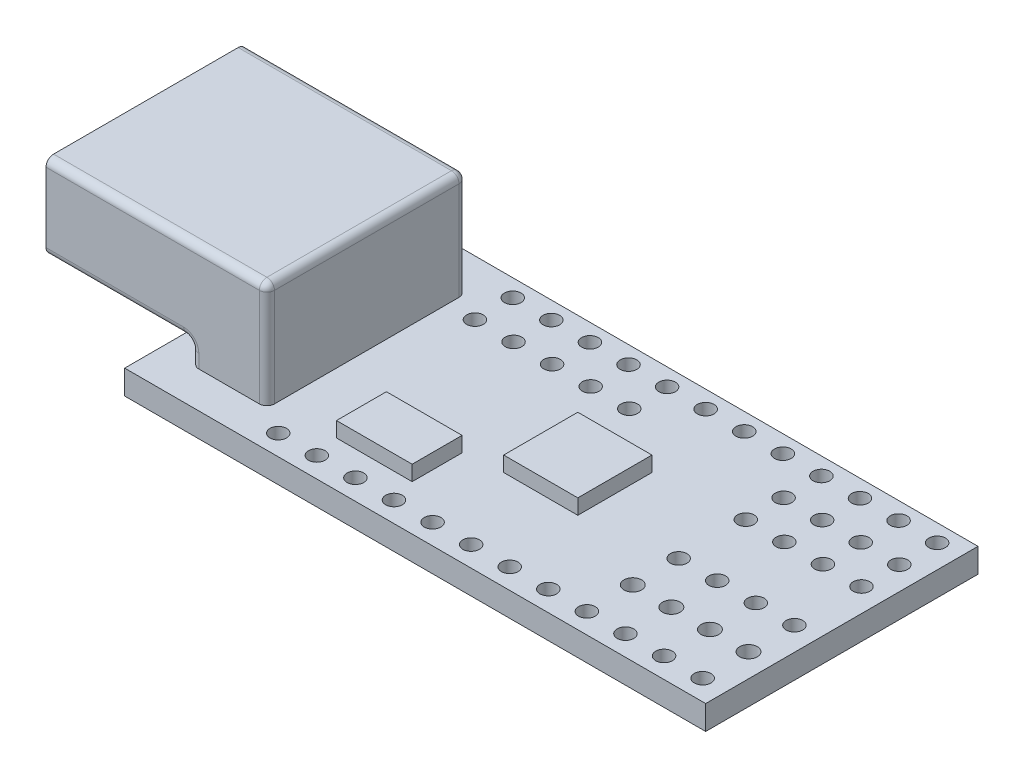
SolidWorks part; units mm, degrees
ref_plane "Plan de face" through (0, 0, 0) normal (0, 0, 1) x (1, 0, 0)
ref_plane "Plan de dessus" through (0, 0, 0) normal (0, 1, 0) x (1, 0, 0)
ref_plane "Plan de droite" through (0, 0, 0) normal (1, 0, 0) x (0, 0, -1)
sketch "Esquisse1" plane through (0, 0, 0) normal (0, 1, 0) x (1, 0, 0)
  line L1 (-19.2, -9) -> (19.2, -9)
  line L2 (-19.2, -9) -> (-19.2, 9)
  line L3 (-19.2, 9) -> (19.2, 9)
  line L4 (19.2, -9) -> (19.2, 9)
  circle A0 centre (17.65, -7.65) radius 0.55
  circle A1 centre (15.1, -7.65) radius 0.55
  circle A2 centre (12.55, -7.65) radius 0.55
  circle A3 centre (10, -7.65) radius 0.55
  circle A4 centre (7.45, -7.65) radius 0.55
  circle A5 centre (4.9, -7.65) radius 0.55
  circle A6 centre (2.35, -7.65) radius 0.55
  circle A7 centre (-0.2, -7.65) radius 0.55
  circle A8 centre (-2.75, -7.65) radius 0.55
  circle A9 centre (-5.3, -7.65) radius 0.55
  circle A10 centre (-7.85, -7.65) radius 0.55
  circle A11 centre (-10.4, -7.65) radius 0.55
  circle A12 centre (17.65, 7.85) radius 0.55
  circle A13 centre (15.1, 7.85) radius 0.55
  circle A14 centre (12.55, 7.85) radius 0.55
  circle A15 centre (10, 7.85) radius 0.55
  circle A16 centre (7.45, 7.85) radius 0.55
  circle A17 centre (4.9, 7.85) radius 0.55
  circle A18 centre (2.35, 7.85) radius 0.55
  circle A19 centre (-0.2, 7.85) radius 0.55
  circle A20 centre (-2.75, 7.85) radius 0.55
  circle A21 centre (-5.3, 7.85) radius 0.55
  circle A22 centre (-7.85, 7.85) radius 0.55
  circle A23 centre (-10.4, 7.85) radius 0.55
  circle A24 centre (17.65, -4.6173) radius 0.5827
  circle A25 centre (17.65, -1.5845) radius 0.55
  circle A26 centre (17.65, 5.35) radius 0.55
  circle A27 centre (17.65, 2.85) radius 0.55
  circle A28 centre (15.1, -4.6173) radius 0.5827
  circle A29 centre (12.55, -4.6173) radius 0.5827
  circle A30 centre (10, -4.6173) radius 0.5827
  circle A31 centre (15.1, -1.5845) radius 0.55
  circle A32 centre (12.55, -1.5845) radius 0.55
  circle A33 centre (10, -1.5845) radius 0.55
  circle A34 centre (15.1, 5.35) radius 0.55
  circle A35 centre (15.1, 2.85) radius 0.55
  circle A36 centre (12.55, 5.35) radius 0.55
  circle A37 centre (12.55, 2.85) radius 0.55
  circle A38 centre (10, 5.35) radius 0.55
  circle A39 centre (10, 2.85) radius 0.55
  circle A40 centre (-10.4, 5.35) radius 0.55
  circle A41 centre (-7.85, 5.35) radius 0.55
  circle A42 centre (-5.3, 5.35) radius 0.55
  circle A43 centre (-2.75, 5.35) radius 0.55
  circle A44 centre (-0.2, 5.35) radius 0.55
  point P0 (0, 0)
  point P6 (0, 9)
  point P7 (-19.2, 0)
  point P10 (18.2, -7.65)
  point P11 (17.65, -8.2)
  point P36 (18.2, 7.85)
  point P37 (17.65, 8.4)
  point P68 (17.65, 3.4)
  point P69 (17.65, 5.9)
  point P70 (17.65, 7.3)
  point P71 (17.65, -7.1)
  point P72 (17.65, -5.2)
  point P73 (17.65, 4.8)
  point P74 (17.65, -4.0345)
  point P75 (17.65, -2.1345)
  dimension "D3" = 1.1
  dimension "D8" = 1.1
  dimension "D13" = 1.1
  dimension "D14" = 1.1
  dimension "D15" = 1.1
  dimension "D16" = 1.1655
  dimension "D27" = 1.1
  dimension "D1" = 18
  dimension "D2" = 38.4
  dimension "D4" = 1
  dimension "D5" = 0.8
  dimension "D7" = 2.55
  dimension "D9" = 1
  dimension "D10" = 0.6
  dimension "D12" = 2.55
  dimension "D17" = 1.4
  dimension "D18" = 1.4
  dimension "D19" = 1.9
  dimension "D20" = 1.9
  dimension "D22" = 2.55
  dimension "D24" = 2.55
  dimension "D26" = 2.55
  dimension "D29" = 2.55
  dimension "D6" = 12
  dimension "D11" = 12
  dimension "D21" = 4
  dimension "D23" = 4
  dimension "D25" = 4
  dimension "D28" = 5
extrude "Boss.-Extru.1" add sketch "Esquisse1" along normal blind 1.6
sketch "Esquisse2" plane through (0, 1.6, 0) normal (0, 1, 0) x (1, 0, 0)
  line L0 (-19.2, -9) -> (19.2, -9) construction
  line L1 (-8.2, -6) -> (-3.2, -6)
  line L2 (-8.2, -6) -> (-8.2, -2.7)
  line L3 (-8.2, -2.7) -> (-3.2, -2.7)
  line L4 (-3.2, -6) -> (-3.2, -2.7)
  line L5 (-8.2, -6) -> (-3.2, -2.7) construction
  line L6 (-8.2, -2.7) -> (-3.2, -6) construction
  line L7 (-19.2, 9) -> (-19.2, -9) construction
  line L8 (19.2, -9) -> (19.2, 9) construction
  line L9 (-0.7, -2.45) -> (4.2, -2.45)
  line L10 (-0.7, -2.45) -> (-0.7, 2.45)
  line L11 (-0.7, 2.45) -> (4.2, 2.45)
  line L12 (4.2, -2.45) -> (4.2, 2.45)
  line L13 (-0.7, -2.45) -> (4.2, 2.45) construction
  line L14 (-0.7, 2.45) -> (4.2, -2.45) construction
  point P0 (-5.7, -4.35)
  point P9 (-3.2, -4.35)
  point P10 (1.75, 0)
  point P17 (-19.2, 0)
  dimension "D1" = 3
  dimension "D2" = 11
  dimension "D3" = 3.3
  dimension "D4" = 5
  dimension "D5" = 4.9
  dimension "D6" = 4.9
  dimension "D7" = 15
extrude "Boss.-Extru.2" add sketch "Esquisse2" along normal blind 1
sketch "Esquisse3" plane through (0, 1.6, 0) normal (0, 1, 0) x (1, 0, 0)
  line L0 (19.2, -9) -> (19.2, 9) construction
  line L1 (-17.2, -6.6) -> (-12.2, -6.6)
  line L2 (-17.2, -6.6) -> (-17.2, 6.6)
  line L3 (-17.2, 6.6) -> (-12.2, 6.6)
  line L4 (-12.2, -6.6) -> (-12.2, 6.6)
  line L5 (-17.2, -6.6) -> (-12.2, 6.6) construction
  line L6 (-17.2, 6.6) -> (-12.2, -6.6) construction
  line L7 (-19.2, 9) -> (-19.2, -9) construction
  point P0 (-14.7, 0)
  point P7 (19.2, 0)
  dimension "D1" = 13.2
  dimension "D2" = 5
  dimension "D3" = 7
extrude "Boss.-Extru.3" add sketch "Esquisse3" along normal blind 7
sketch "Esquisse4" plane through (-17.2, 0, 0) normal (-1, 0, 0) x (0, 0, 1)
  line L0 (6.6, 8.6) -> (6.6, 1.6) construction
  line L1 (-6.6, 8.6) -> (6.6, 8.6)
  line L2 (-6.6, 8.6) -> (-6.6, 3)
  line L3 (-6.6, 3) -> (6.6, 3)
  line L4 (6.6, 8.6) -> (6.6, 3)
  dimension "D1" = 5.6
extrude "Boss.-Extru.4" add sketch "Esquisse4" along normal blind 9.6
fillet "Congé2" radius 0.5 10 edges at (-17.2, 2.3, -6.6) (-17.2, 2.3, 6.6) (-17.2, 3, 0) (-12.2, 5.1, -6.6) (-12.2, 8.6, 0) (-12.2, 5.1, 6.6) (-22, 3, -6.6) (-22, 3, 6.6) (-19.5, 8.6, -6.6) (-19.5, 8.6, 6.6)
sketch "Esquisse5" plane through (-26.8, 0, 0) normal (-1, 0, 0) x (0, 0, 1)
  line L0 (-6.6, 8.1) -> (-6.6, 3.5) construction
  line L1 (-5.9, 3.7) -> (5.9, 3.7)
  line L2 (-5.9, 3.7) -> (-5.9, 7.9)
  line L3 (-5.9, 7.9) -> (5.9, 7.9)
  line L4 (5.9, 3.7) -> (5.9, 7.9)
  line L5 (-6.1, 3) -> (6.1, 3) construction
  line L6 (6.6, 3.5) -> (6.6, 8.1) construction
  line L7 (6.1, 8.6) -> (-6.1, 8.6) construction
  dimension "D1" = 0.7
  dimension "D2" = 0.7
  dimension "D3" = 0.7
  dimension "D4" = 0.7
extrude "Enlèv. mat.-Extru.1" cut sketch "Esquisse5" against normal blind 9.3
sketch "Esquisse6" plane through (-17.5, 0, 0) normal (-1, 0, 0) x (0, 0, 1)
  line L0 (5.9, 7.9) -> (-5.9, 7.9) construction
  line L1 (-4.9, 7.3) -> (4.9, 7.3)
  line L2 (-4.9, 7.3) -> (-4.9, 5.5)
  line L3 (-4.9, 5.5) -> (4.9, 5.5)
  line L4 (4.9, 7.3) -> (4.9, 5.5)
  line L5 (-5.9, 7.9) -> (-5.9, 3.7) construction
  line L6 (5.9, 3.7) -> (5.9, 7.9) construction
  dimension "D1" = 1.8
  dimension "D2" = 0.6
  dimension "D3" = 1
  dimension "D4" = 1
extrude "Boss.-Extru.5" add sketch "Esquisse6" along normal blind 8.5
